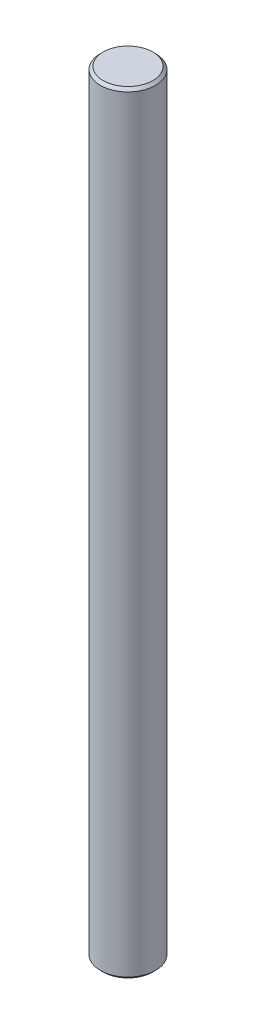
SolidWorks part; units mm, degrees
material "AISI 1045 Steel, cold drawn"
ref_plane "Front Plane" through (0, 0, 0) normal (0, 0, 1) x (1, 0, 0)
ref_plane "Top Plane" through (0, 0, 0) normal (0, 1, 0) x (1, 0, 0)
ref_plane "Right Plane" through (0, 0, 0) normal (1, 0, 0) x (0, 0, -1)
sketch "Sketch1" plane through (0, 0, 0) normal (0, 1, 0) x (1, 0, 0)
  circle A0 centre (0, 0) radius 2.5
  dimension "D1" = 5
extrude "Boss-Extrude1" add sketch "Sketch1" along normal mid plane 70
chamfer "Chamfer1" distance 0.25 angle 45 2 edges at (0, -35, 2.5) (0, 35, 2.5)
